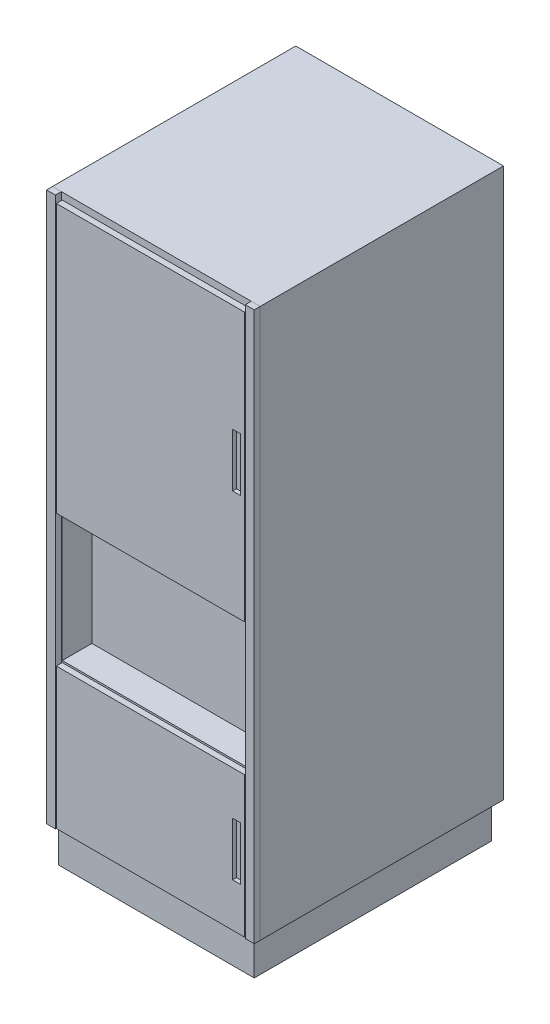
SolidWorks part; units mm, degrees
ref_plane "Front Plane" through (0, 0, 0) normal (0, 0, 1) x (1, 0, 0)
ref_plane "Top Plane" through (0, 0, 0) normal (0, 1, 0) x (1, 0, 0)
ref_plane "Right Plane" through (0, 0, 0) normal (1, 0, 0) x (0, 0, -1)
other "Configuration Table"
sketch "Sketch1" plane through (0, 0, 0) normal (0, 0, 1) x (1, 0, 0)
  line L1 (0, 120) -> (700, 120)
  line L2 (0, 120) -> (0, 1970)
  line L3 (0, 1970) -> (700, 1970)
  line L4 (700, 120) -> (700, 1970)
extrude "govde_kasa" add sketch "Sketch1" against normal blind 820 separate body
sketch "Sketch2" plane through (0, 0, 0) normal (0, 0, 1) x (1, 0, 0)
  line L1 (20, 0) -> (680, 0)
  line L2 (20, 0) -> (20, 120)
  line L3 (20, 120) -> (680, 120)
  line L4 (680, 0) -> (680, 120)
extrude "plint" add sketch "Sketch2" against normal blind 800 separate body
sketch "Sketch3" plane through (0, 0, 0) normal (0, 0, 1) x (1, 0, 0)
  line L1 (0, 120) -> (30, 120)
  line L2 (0, 120) -> (0, 1970)
  line L3 (0, 1970) -> (30, 1970)
  line L4 (30, 120) -> (30, 1970)
extrude "sove_sol" add sketch "Sketch3" along normal blind 20 separate body
sketch "Sketch4" plane through (0, 0, 0) normal (0, 0, 1) x (1, 0, 0)
  line L1 (670, 120) -> (700, 120)
  line L2 (670, 120) -> (670, 1970)
  line L3 (670, 1970) -> (700, 1970)
  line L4 (700, 120) -> (700, 1970)
extrude "sove_sag" add sketch "Sketch4" along normal blind 20 separate body
sketch "Sketch5" plane through (0, 0, 0) normal (0, 0, 1) x (1, 0, 0)
  line L1 (33, 1043) -> (667, 1043)
  line L2 (33, 1043) -> (33, 1947)
  line L3 (33, 1947) -> (667, 1947)
  line L4 (667, 1043) -> (667, 1947)
extrude "kapi_sarjor" add sketch "Sketch5" along normal blind 20 separate body
sketch "Sketch6" plane through (0, 0, 0) normal (0, 0, 1) x (1, 0, 0)
  line L1 (627, 1405) -> (653, 1405)
  line L2 (627, 1405) -> (627, 1585)
  line L3 (627, 1585) -> (653, 1585)
  line L4 (653, 1405) -> (653, 1585)
extrude "kapi_sarjor_kulp" cut sketch "Sketch6" along normal blind 13 from offset 7
sketch "Sketch7" plane through (0, 0, 0) normal (0, 0, 1) x (1, 0, 0)
  line L1 (33, 603) -> (667, 603)
  line L2 (33, 603) -> (33, 1037)
  line L3 (33, 1037) -> (667, 1037)
  line L4 (667, 603) -> (667, 1037)
extrude "aciklik_kutulama" cut sketch "Sketch7" against normal blind 100
sketch "Sketch8" plane through (0, 0, 0) normal (0, 0, 1) x (1, 0, 0)
  line L1 (33, 123) -> (667, 123)
  line L2 (33, 123) -> (33, 597)
  line L3 (33, 597) -> (667, 597)
  line L4 (667, 123) -> (667, 597)
extrude "kapak_pano_mek" add sketch "Sketch8" along normal blind 20 separate body
sketch "Sketch9" plane through (0, 0, 0) normal (0, 0, 1) x (1, 0, 0)
  line L1 (627, 270) -> (653, 270)
  line L2 (627, 270) -> (627, 450)
  line L3 (627, 450) -> (653, 450)
  line L4 (653, 270) -> (653, 450)
extrude "kapak_pano_mek_kulp" cut sketch "Sketch9" along normal blind 13 from offset 7
